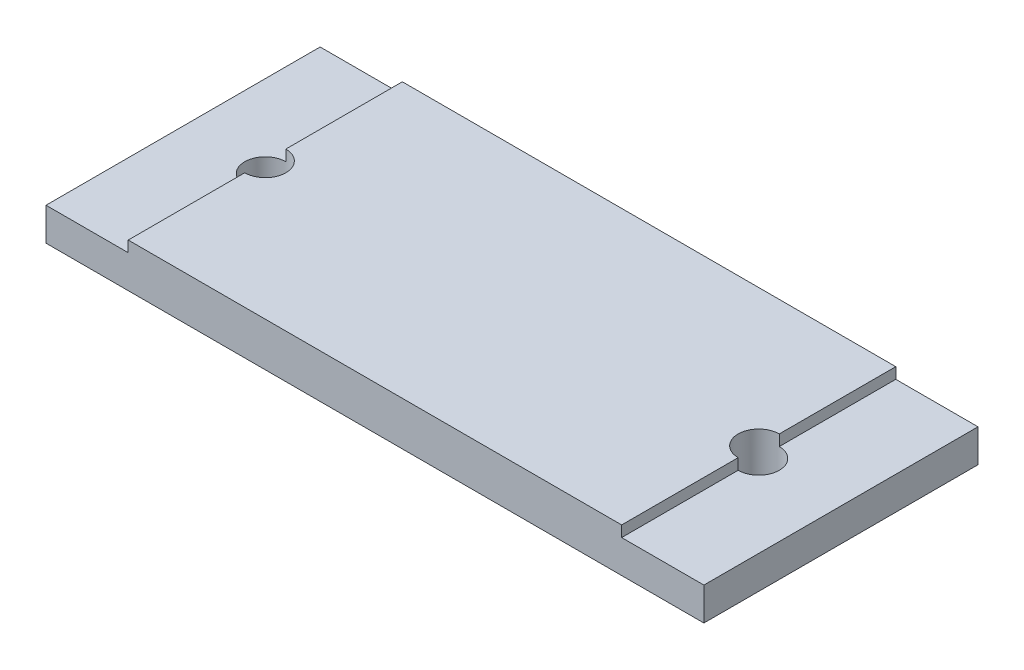
SolidWorks part; units mm, degrees
material "6061-T6 (SS)"
ref_plane "Front Plane" through (0, 0, 0) normal (0, 0, 1) x (1, 0, 0)
ref_plane "Top Plane" through (0, 0, 0) normal (0, 1, 0) x (1, 0, 0)
ref_plane "Right Plane" through (0, 0, 0) normal (1, 0, 0) x (0, 0, -1)
sketch "Sketch2" plane through (0, 0, 0) normal (0, 1, 0) x (1, 0, 0)
  line L1 (0, 0) -> (304.8, 0)
  line L2 (0, 0) -> (0, -127)
  line L3 (0, -127) -> (304.8, -127)
  line L4 (304.8, 0) -> (304.8, -127)
  circle A0 centre (38.1, -63.5) radius 9.525
  circle A1 centre (266.7, -63.5) radius 9.525
  point P13 (0, -63.5)
  point P14 (304.8, -63.5)
  dimension "D3" = 19.05
  dimension "D4" = 19.05
  dimension "D1" = 304.8
  dimension "D2" = 127
  dimension "D5" = 38.1
  dimension "D6" = 38.1
extrude "Boss-Extrude1" add sketch "Sketch2" along normal blind 15.24
sketch "Sketch3" plane through (0, 15.24, 0) normal (0, 1, 0) x (1, 0, 0)
  line L0 (304.8, 0) -> (0, 0) construction
  line L1 (38.1, 0) -> (266.7, 0)
  line L2 (38.1, 0) -> (38.1, -53.975)
  line L3 (38.1, -127) -> (266.7, -127)
  line L4 (266.7, 0) -> (266.7, -53.975)
  line L5 (0, -127) -> (304.8, -127) construction
  line L6 (0, 0) -> (0, -127) construction
  line L7 (304.8, -127) -> (304.8, 0) construction
  line L8 (38.1, -73.025) -> (38.1, -127)
  line L9 (266.7, -73.025) -> (266.7, -127)
  circle A5 centre (38.1, -63.5) radius 9.525 construction
  circle A6 centre (266.7, -63.5) radius 9.525 construction
  arc A7 (38.1, -73.025) -> (38.1, -53.975) centre (38.1, -63.5) ccw
  arc A8 (266.7, -53.975) -> (266.7, -73.025) centre (266.7, -63.5) ccw
  dimension "D1" = 38.1
  dimension "D2" = 38.1
extrude "Boss-Extrude2" add sketch "Sketch3" along normal blind 5.08
equation "\"t\"= 5in'Thickness (in)"
equation "\"L\"= 12in'Length (in)"
equation "\"Dis\"= 9in'Distance between holes(In)"
equation "\"D\"= .75in'Diameter(In)"
equation "\"F\"= 224.809'Load (lbs)"
equation "\"C\"= 1.5in'Distance from hole to end(in)"
equation "\"E\"= 10 * 10 ^ 6'Modulus of Elastisity (PSI)"
equation "\"Y\"= .003937in'max deflection(In)"
equation "\"H\"= .6'Hight (in)"
equation "\"D1@Sketch2\"=\"L\""
equation "\"D2@Sketch2\"=\"t\""
equation "\"D5@Sketch2\"=\"C\""
equation "\"D6@Sketch2\"=\"C\""
equation "\"D1@Boss-Extrude1\"=\"H\""
